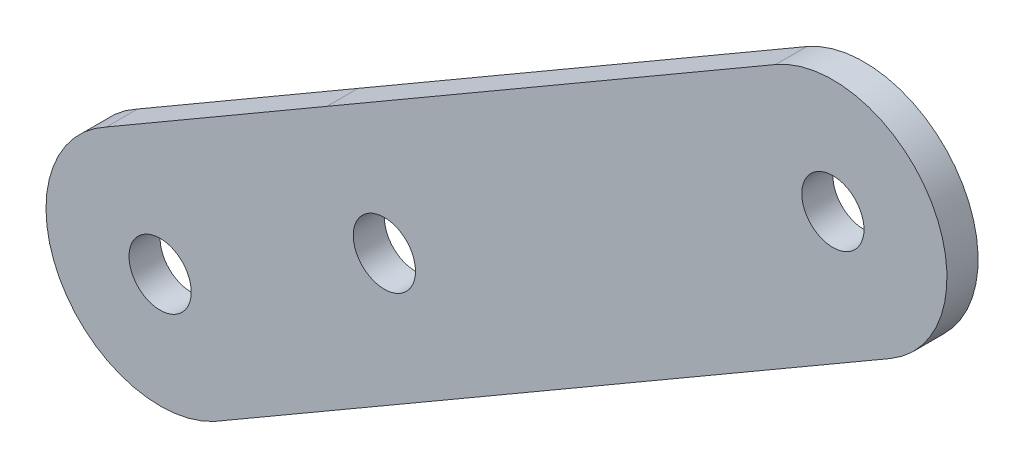
SolidWorks part; units mm, degrees
ref_plane "Front Plane" through (0, 0, 0) normal (0, 0, 1) x (1, 0, 0)
ref_plane "Top Plane" through (0, 0, 0) normal (0, 1, 0) x (1, 0, 0)
ref_plane "Right Plane" through (0, 0, 0) normal (1, 0, 0) x (0, 0, -1)
sketch "Sketch1" plane through (0, 0, 0) normal (0, 0, 1) x (1, 0, 0)
  line L0 (146.5479, -69.5024) -> (151.7287, -79.2059) construction
  line L1 (151.7287, -79.2059) -> (141.3671, -59.7988) construction
  line L2 (141.3671, -59.7988) -> (162.6406, -47.4373)
  line L3 (151.7287, -79.2059) -> (173.6884, -66.4622)
  line L4 (162.6406, -47.4373) -> (205.8819, -22.3274)
  line L5 (173.6884, -66.4622) -> (216.9295, -41.3523)
  arc A0 (141.3671, -59.7988) -> (152.4026, -78.8149) centre (146.5479, -69.5024) ccw
  circle A2 centre (146.5479, -69.5024) radius 3
  circle A4 centre (168.1672, -56.9482) radius 3
  arc A6 (216.9295, -41.3523) -> (205.8819, -22.3274) centre (211.4057, -31.8398) ccw
  circle A8 centre (168.1672, -56.9482) radius 3 construction
  circle A9 centre (211.4057, -31.8398) radius 3
  dimension "D1" = 22
  dimension "D3" = 11
  dimension "D2" = 50
extrude "Boss-Extrude1" add sketch "Sketch1" along normal blind 3 contours L5 A6 L4 L2 A0 L3 A9 A2 A4
